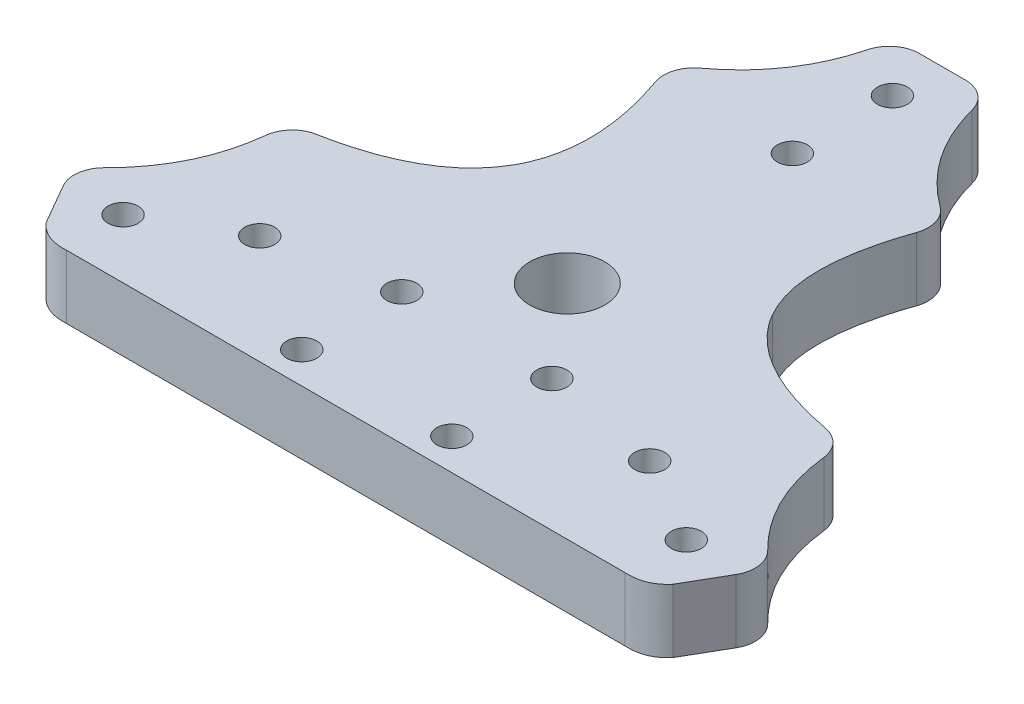
SolidWorks part; units mm, degrees
ref_plane "Front Plane" through (0, 0, 0) normal (0, 0, 1) x (1, 0, 0)
ref_plane "Top Plane" through (0, 0, 0) normal (0, 1, 0) x (1, 0, 0)
ref_plane "Right Plane" through (0, 0, 0) normal (1, 0, 0) x (0, 0, -1)
sketch "Sketch1" plane through (0, 0, 0) normal (0, 1, 0) x (1, 0, 0)
  line L14 (4.6287, 75) -> (-4.6287, 75)
  line L28 (55.8476, -44.2931) -> (-55.8476, -44.2931)
  line L32 (62.6375, -41.5086) -> (67.2663, -33.4914)
  line L35 (-67.2663, -33.4914) -> (-62.6375, -41.5086)
  circle A15 centre (0, 0) radius 7.5
  circle A16 centre (0, 65) radius 3
  circle A17 centre (0, 45) radius 3
  circle A18 centre (56.2917, -32.5) radius 3
  circle A19 centre (38.9711, -22.5) radius 3
  circle A20 centre (-56.2917, -32.5) radius 3
  circle A21 centre (-38.9711, -22.5) radius 3
  arc A22 (50.9138, 0.7293) -> (55.7675, -4.4972) centre (49.8051, -5.1674) cw
  arc A23 (66.2827, -26.219) -> (67.2663, -33.4914) centre (62.0701, -30.4914) cw
  arc A28 (-67.2663, -33.4914) -> (-66.2827, -26.219) centre (-62.0701, -30.4914) cw
  arc A29 (-55.7675, -4.4972) -> (-50.9138, 0.7293) centre (-49.8051, -5.1674) cw
  arc A30 (-26.0885, 43.728) -> (-23.9891, 50.5447) centre (-20.4275, 45.7161) cw
  arc A31 (26.0885, 43.728) -> (23.9891, 50.5447) centre (20.4275, 45.7161) ccw
  arc A32 (10.4351, 70.512) -> (4.6287, 75) centre (4.6287, 69) ccw
  arc A33 (-4.6287, 75) -> (-10.4351, 70.512) centre (-4.6287, 69) ccw
  circle A34 centre (-15.0755, -18) radius 3
  circle A35 centre (-15.0755, -38) radius 3
  circle A36 centre (14.9245, -38) radius 3
  circle A37 centre (14.9245, -18) radius 3
  spline S0 degree 3 poles (-10.4351, 70.512) (-11.4369, 66.6649) (-14.6918, 59.1703) (-20.3192, 53.2517) (-23.9891, 50.5447) knots 0.130555 0.130555 0.130555 0.130555 0.477566 0.872598 0.872598 0.872598 0.872598
  spline S1 degree 3 poles (26.0885, 43.728) (23.9838, 37.7352) (21.8612, 26.9544) (23.912, 18.5832) (25.9808, 15) knots 0.052698 0.052698 0.052698 0.052698 0.276349 0.5 0.5 0.5 0.5
  spline S2 degree 3 poles (10.4351, 70.512) (11.4369, 66.6649) (14.6918, 59.1703) (20.3192, 53.2517) (23.9891, 50.5447) knots 0.130555 0.130555 0.130555 0.130555 0.477566 0.872598 0.872598 0.872598 0.872598
  spline S3 degree 3 poles (50.9138, 0.7293) (44.6715, 1.903) (34.2738, 5.4551) (28.0495, 11.4168) (25.9808, 15) knots 0.052698 0.052698 0.052698 0.052698 0.276349 0.5 0.5 0.5 0.5
  spline S4 degree 3 poles (66.2827, -26.219) (63.452, -23.4278) (58.5889, -16.8617) (56.2769, -9.029) (55.7675, -4.4972) knots 0.130555 0.130555 0.130555 0.130555 0.477566 0.872598 0.872598 0.872598 0.872598
  spline S5 degree 2 poles (62.6375, -41.5086) (60.1104, -44.5189) (55.8476, -44.2931) knots 0 0 0 1 1 1
  spline S6 degree 3 poles (-26.0885, 43.728) (-23.9838, 37.7352) (-21.8612, 26.9544) (-23.912, 18.5832) (-25.9808, 15) knots 0.052698 0.052698 0.052698 0.052698 0.276349 0.5 0.5 0.5 0.5
  spline S7 degree 2 poles (-62.6375, -41.5086) (-60.1104, -44.5189) (-55.8476, -44.2931) knots 0 0 0 1 1 1
  spline S10 degree 3 poles (-66.2827, -26.219) (-63.452, -23.4278) (-58.5889, -16.8617) (-56.2769, -9.029) (-55.7675, -4.4972) knots 0.130555 0.130555 0.130555 0.130555 0.477566 0.872598 0.872598 0.872598 0.872598
  spline S11 degree 3 poles (-50.9138, 0.7293) (-44.6715, 1.903) (-34.2738, 5.4551) (-28.0495, 11.4168) (-25.9808, 15) knots 0.052698 0.052698 0.052698 0.052698 0.276349 0.5 0.5 0.5 0.5
  point P4 (0, 75)
  point P11 (0.0755, -2.747)
  point P19 (0, 0)
  point P24 (0, 0)
  point P27 (0, 0)
  point P33 (0, 0)
  point P43 (0, 0)
  point P47 (-0.0755, -2.747)
  point P67 (0, 0)
  dimension "D1" = 3
  dimension "D3" = 20
  dimension "D5" = 20
  dimension "D2" = 10
  dimension "D6" = 18
  dimension "D4" = 3
extrude "Boss-Extrude1" add sketch "Sketch1" along normal blind 12.7
